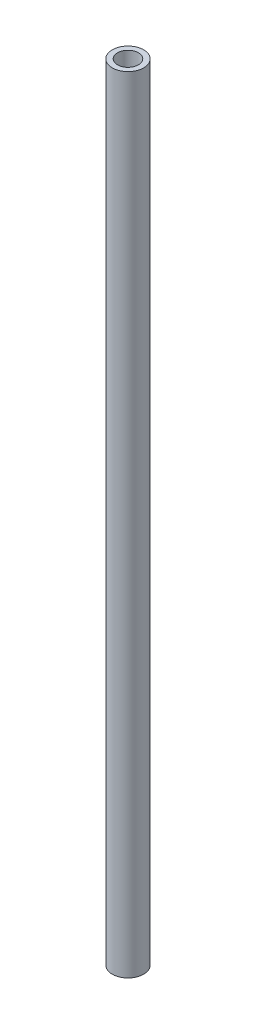
SolidWorks part; units mm, degrees
material "Thornel Mat VMA"
ref_plane "Front Plane" through (0, 0, 0) normal (0, 0, 1) x (1, 0, 0)
ref_plane "Top Plane" through (0, 0, 0) normal (0, 1, 0) x (1, 0, 0)
ref_plane "Right Plane" through (0, 0, 0) normal (1, 0, 0) x (0, 0, -1)
sketch "Sketch1" plane through (0, 0, 0) normal (0, 1, 0) x (1, 0, 0)
  circle A0 centre (0, 0) radius 6
  circle A1 centre (0, 0) radius 4
  dimension "D1" = 12
  dimension "D2" = 8
extrude "Boss-Extrude1" add sketch "Sketch1" along normal mid plane 300
